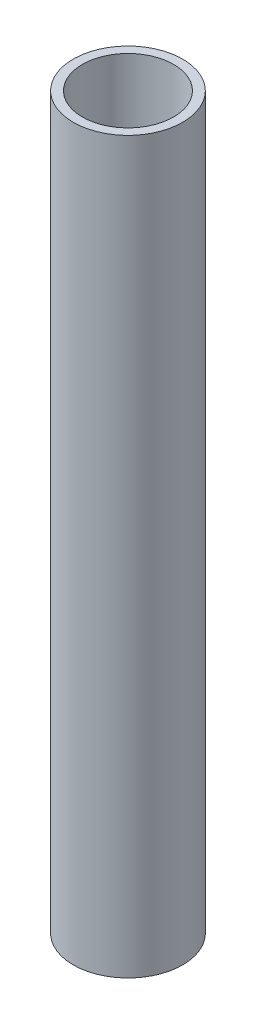
SolidWorks part; units mm, degrees
ref_plane "Front Plane" through (0, 0, 0) normal (0, 0, 1) x (1, 0, 0)
ref_plane "Top Plane" through (0, 0, 0) normal (0, 1, 0) x (1, 0, 0)
ref_plane "Right Plane" through (0, 0, 0) normal (1, 0, 0) x (0, 0, -1)
sketch "Sketch1" plane through (0, 0, 0) normal (0, 0, 1) x (1, 0, 0)
  line L0 (0, 0) -> (15, 0)
  line L1 (15, 0) -> (15, 200)
  line L3 (0, 200) -> (0, 0)
  line L5 (0, 200) -> (15, 200)
  dimension "D1" = 200
  dimension "D2" = 15
revolve "Revolve1" add sketch "Sketch1" angle 360 about L3
sketch "Sketch2" plane through (0, 200, 0) normal (0, 1, 0) x (1, 0, 0)
  circle A0 centre (0, 0) radius 12.5
  dimension "D1" = 25
extrude "Cut-Extrude1" cut sketch "Sketch2" against normal blind 180
